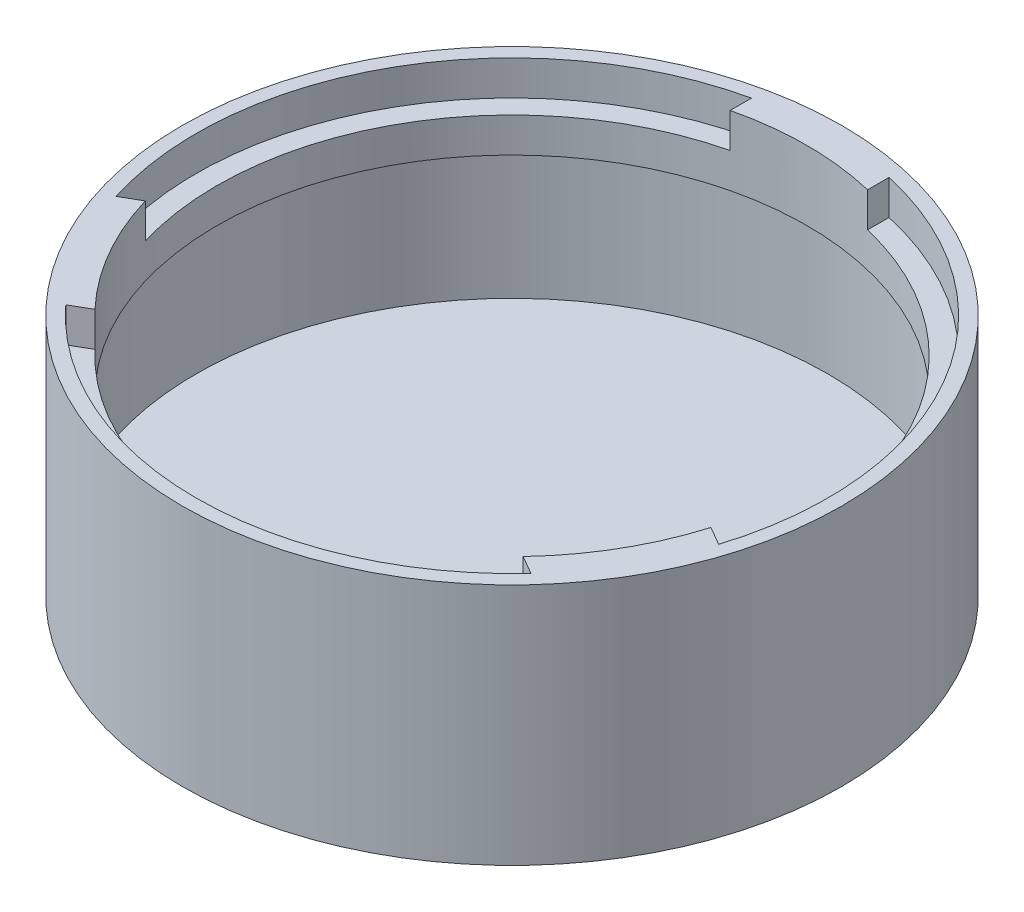
SolidWorks part; units mm, degrees
ref_plane "Alzado" through (0, 0, 0) normal (0, 0, 1) x (1, 0, 0)
ref_plane "Planta" through (0, 0, 0) normal (0, 1, 0) x (1, 0, 0)
ref_plane "Vista lateral" through (0, 0, 0) normal (1, 0, 0) x (0, 0, -1)
sketch "Croquis1" plane through (0, 0, 0) normal (0, 1, 0) x (1, 0, 0)
  circle A0 centre (0, 0) radius 95
  dimension "D1" = 190
extrude "Saliente-Extruir1" add sketch "Croquis1" along normal blind 10
sketch "Croquis3" plane through (0, 10, 0) normal (0, 1, 0) x (1, 0, 0)
  circle A0 centre (0, 0) radius 91
  circle A1 centre (0, 0) radius 95
  circle A2 centre (0, 0) radius 95
  dimension "D2" = 182
  dimension "D1" = 0
extrude "Saliente-Extruir2" add sketch "Croquis3" along normal blind 60
ref_plane "Plano1" through (0, 60, 0) normal (0, 1, 0) x (1, 0, 0)
sketch "Croquis4" plane through (0, 60, 0) normal (0, 1, 0) x (1, 0, 0)
  line L6 (0, 0) -> (0, 91) construction
  line L7 (0, 0) -> (78.8083, -45.5) construction
  line L8 (0, 0) -> (-78.8083, -45.5) construction
  line L9 (-86.8202, -27.2626) -> (-81.4871, -24.1836)
  line L10 (-67.0202, -61.5572) -> (-61.6871, -58.4782)
  line L11 (81.4871, -24.1836) -> (86.8202, -27.2626)
  line L12 (61.6871, -58.4782) -> (67.0202, -61.5572)
  line L13 (-19.8, 82.6617) -> (0, 85) construction
  line L14 (-19.8, 88.8198) -> (0, 91) construction
  line L15 (0, 85) -> (19.8, 82.6617) construction
  line L16 (19.8, 88.8198) -> (0, 91) construction
  line L17 (-19.8, 88.8198) -> (-19.8, 82.6617)
  line L18 (19.8, 88.8198) -> (19.8, 82.6617)
  circle A7 centre (0, 0) radius 85
  circle A8 centre (0, 0) radius 91 construction
  circle A9 centre (0, 0) radius 91
  dimension "D1" = 170
  dimension "D2" = 120
  dimension "D3" = 120
  dimension "D4" = 19.8
  dimension "D5" = 19.8
  dimension "D6" = 19.8
  dimension "D7" = 19.8
  dimension "D8" = 19.8
  dimension "D9" = 19.8
  dimension "D10" = 19.8
  dimension "D11" = 19.8
extrude "Saliente-Extruir10" add sketch "Croquis4" along normal blind 10 contours L9 A9 L10 A7 | L12 A9 L11 A7 | L18 A9 L17 A7
sketch "Croquis7" plane through (0, 60, 0) normal (0, 1, 0) x (1, 0, 0)
  circle A0 centre (0, 0) radius 85
  circle A1 centre (0, 0) radius 91
  dimension "D1" = 170
  dimension "D2" = 182
extrude "Saliente-Extruir15" add sketch "Croquis7" against normal blind 10
